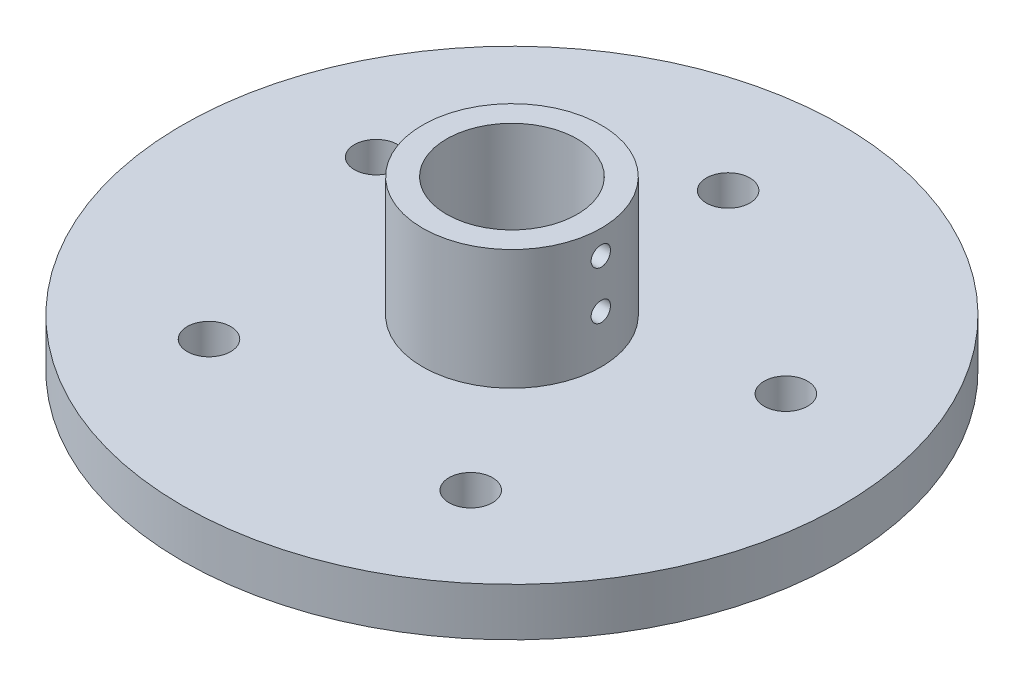
SolidWorks part; units mm, degrees
material "Delrin 2700 NC010, Low Viscosity Acetal Copolymer (SS)"
ref_plane "Front Plane" through (0, 0, 0) normal (0, 0, 1) x (1, 0, 0)
ref_plane "Top Plane" through (0, 0, 0) normal (0, 1, 0) x (1, 0, 0)
ref_plane "Right Plane" through (0, 0, 0) normal (1, 0, 0) x (0, 0, -1)
sketch "Sketch1" plane through (0, 0, 0) normal (0, 0, 1) x (1, 0, 0)
  line L0 (0, 7.8095) -> (0, 0) construction
  line L1 (0, 0) -> (17.272, 0) construction
  line L3 (17.272, 0) -> (87.122, 0)
  line L4 (17.272, 0) -> (17.272, 12.7)
  line L5 (17.272, 12.7) -> (87.122, 12.7)
  line L6 (87.122, 0) -> (87.122, 12.7)
  line L7 (17.272, 12.7) -> (23.622, 12.7)
  line L8 (17.272, 12.7) -> (17.272, 44.45)
  line L9 (17.272, 44.45) -> (23.622, 44.45)
  line L10 (23.622, 12.7) -> (23.622, 44.45)
  dimension "D1" = 17.272
  dimension "D2" = 12.7
  dimension "D3" = 6.35
  dimension "D4" = 31.75
  dimension "5.5" = 69.85
revolve "Revolve1" add sketch "Sketch1" angle 360 about L0
sketch "Sketch2" plane through (0, 12.7, 0) normal (0, 1, 0) x (1, 0, 0)
  line L0 (0, 57.15) -> (54.1556, 18.2562) construction
  line L1 (54.1556, 18.2562) -> (34.5994, -45.4863) construction
  line L2 (34.5994, -45.4863) -> (-34.5994, -45.4863) construction
  line L3 (-34.5994, -45.4863) -> (-54.1556, 18.2562) construction
  line L4 (-54.1556, 18.2562) -> (0, 57.15) construction
  circle A0 centre (0, 0) radius 57.15 construction
  point P3 (-54.1556, 18.2562)
  point P4 (0, 57.15)
  point P5 (54.1556, 18.2562)
  point P6 (-34.5994, -45.4863)
  point P7 (34.5994, -45.4863)
  dimension "D1" = 114.3
  dimension "D2" = 66.675
hole_wizard "1/2-20 Tapped Hole1" positions "Sketch3" profile "Sketch4" tap size "1/2-20" standard "ANSI Inch" end condition through all
sketch "Sketch3" plane through (0, 12.7, 0) normal (0, 1, 0) x (1, 0, 0)
  point P0 (-54.1556, 18.2562)
  point P3 (0, 57.15)
  point P6 (54.1556, 18.2562)
  point P9 (34.5994, -45.4863)
  point P12 (-34.5994, -45.4863)
sketch "Sketch4" plane through (-54.1556, 12.7, -18.2562) normal (1, 0, 0) x (0, 0, 1)
  line L0 (0, 0) -> (0, 12.7)
  line L1 (0, 12.7) -> (5.7544, 12.7)
  line L2 (5.7544, 12.7) -> (5.7544, 0)
  line L5 (5.7544, 0) -> (0, 0)
  line L11 (0, -6.35) -> (0, 107.95) construction
  dimension "Thru Tap Drill Dia." = 11.5087
  dimension "Thru Tap Drill Depth" = 12.7
cosmetic thread "Hole Thread1" parameters "D2"=12.7
cosmetic thread "Hole Thread2" parameters "D2"=12.7
cosmetic thread "Hole Thread3" parameters "D2"=12.7
cosmetic thread "Hole Thread4" parameters "D2"=12.7
cosmetic thread "Hole Thread5" parameters "D2"=12.7
hole_wizard "1/4-20 Tapped Hole1" positions "Sketch6" profile "Sketch7" tap size "1/4-20" standard "ANSI Inch"
sketch "Sketch6" plane through (0, 0, 0) normal (1, 0, 0) x (0, 0, -1)
  point P0 (0, 38.1)
  point P5 (0, 25.4)
  point P8 (0, 0)
  point P9 (0, 0)
  dimension "D1" = 38.1
  dimension "D2" = 25.4
sketch "Sketch7" plane through (0, 38.1, 0) normal (0, 1, 0) x (0, 0, 1)
  line L0 (0, 0) -> (0, 87.122)
  line L1 (0, 87.122) -> (2.5527, 87.122)
  line L2 (2.5527, 87.122) -> (2.5527, 0)
  line L5 (2.5527, 0) -> (0, 0)
  line L11 (0, -6.35) -> (0, 107.95) construction
  dimension "Thru Tap Drill Dia." = 5.1054
  dimension "Thru Tap Drill Depth" = 87.122
cosmetic thread "Hole Thread6" parameters "D2"=6.35
cosmetic thread "Hole Thread7" parameters "D2"=6.35
